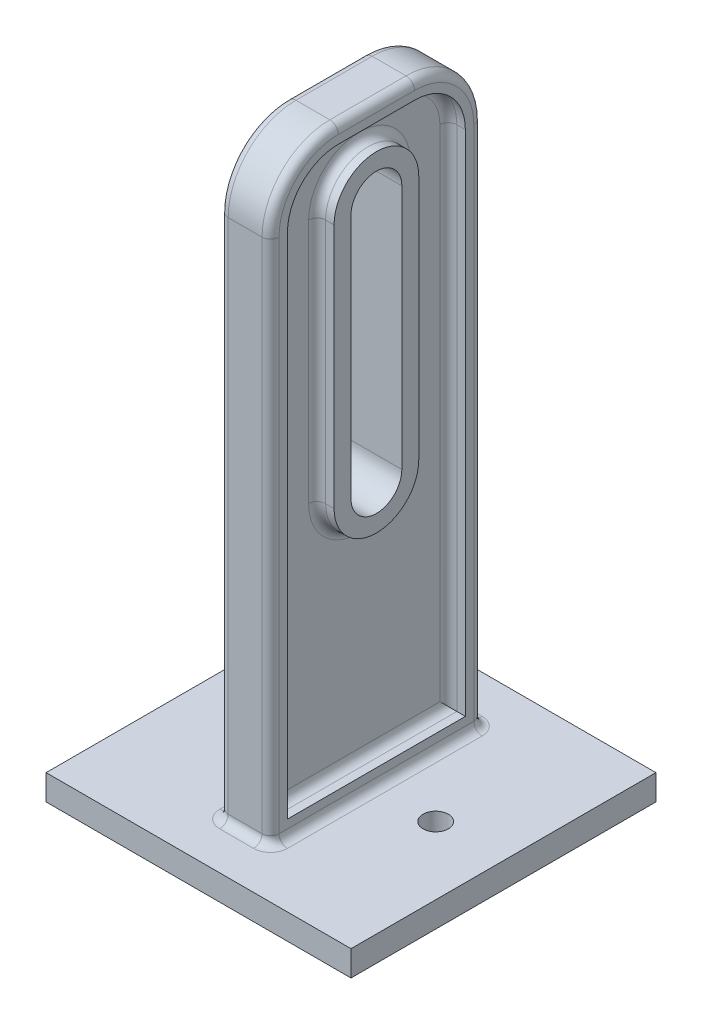
SolidWorks part; units mm, degrees
ref_plane "Front Plane" through (0, 0, 0) normal (0, 0, 1) x (1, 0, 0)
ref_plane "Top Plane" through (0, 0, 0) normal (0, 1, 0) x (1, 0, 0)
ref_plane "Right Plane" through (0, 0, 0) normal (1, 0, 0) x (0, 0, -1)
sketch "Sketch1" plane through (0, 0, 0) normal (0, 1, 0) x (1, 0, 0)
  line L1 (-18, 18) -> (18, 18)
  line L2 (-18, 18) -> (-18, -18)
  line L3 (-18, -18) -> (18, -18)
  line L4 (18, 18) -> (18, -18)
  line L5 (-18, 18) -> (18, -18) construction
  line L6 (-18, -18) -> (18, 18) construction
  point P0 (0, 0)
  dimension "D1" = 36
extrude "Boss-Extrude1" add sketch "Sketch1" along normal blind 3
sketch "Sketch2" plane through (0, 3, 0) normal (0, 1, 0) x (1, 0, 0)
  line L0 (-10, 0) -> (10, 0) construction
  circle A0 centre (-10, 0) radius 1.5
  circle A1 centre (10, 0) radius 1.5
  dimension "D1" = 3
  dimension "D2" = 20
extrude "Cut-Extrude1" cut sketch "Sketch2" against normal through all
sketch "Sketch3" plane through (0, 3, 0) normal (0, 1, 0) x (1, 0, 0)
  line L1 (-3, 12.5) -> (3, 12.5)
  line L2 (-3, 12.5) -> (-3, -12.5)
  line L3 (-3, -12.5) -> (3, -12.5)
  line L4 (3, 12.5) -> (3, -12.5)
  line L5 (-3, 12.5) -> (3, -12.5) construction
  line L6 (-3, -12.5) -> (3, 12.5) construction
  point P0 (0, 0)
  dimension "D1" = 6
  dimension "D2" = 25
extrude "Boss-Extrude2" add sketch "Sketch3" along normal blind 70
sketch "Sketch4" plane through (-3, 0, 0) normal (-1, 0, 0) x (0, 0, 1)
  line L0 (-12.5, 73) -> (12.5, 73) construction
  line L2 (-3, 63) -> (-3, 34)
  line L4 (3, 63) -> (3, 34)
  arc A0 (3, 63) -> (-3, 63) centre (0, 63) ccw
  arc A1 (-3, 34) -> (3, 34) centre (0, 34) ccw
  point P8 (0, 0)
  point P9 (0, 0)
  dimension "D1" = 3
  dimension "D3" = 29
  dimension "D2" = 10
extrude "Cut-Extrude2" cut sketch "Sketch4" against normal through all
fillet "Fillet1" radius 8 2 edges at (0, 73, -12.5) (0, 73, 12.5)
sketch "Sketch5" plane through (-3, 0, 0) normal (-1, 0, 0) x (0, 0, 1)
  line L18 (5, 34) -> (5, 63)
  line L19 (-5, 63) -> (-5, 34)
  line L20 (5, 34) -> (5, 63)
  line L21 (-5, 63) -> (-5, 34)
  line L37 (-10.5, 5) -> (10.5, 5)
  line L38 (10.5, 5) -> (10.5, 65)
  line L39 (4.5, 71) -> (-4.5, 71)
  line L40 (-10.5, 65) -> (-10.5, 5)
  line L41 (-10.5, 5) -> (10.5, 5)
  line L42 (10.5, 5) -> (10.5, 65)
  line L43 (4.5, 71) -> (-4.5, 71)
  line L44 (-10.5, 65) -> (-10.5, 5)
  arc A9 (5, 63) -> (-5, 63) centre (0, 63) ccw
  arc A10 (-5, 34) -> (5, 34) centre (0, 34) ccw
  arc A11 (5, 63) -> (-5, 63) centre (0, 63) ccw
  arc A12 (-5, 34) -> (5, 34) centre (0, 34) ccw
  arc A21 (10.5, 65) -> (4.5, 71) centre (4.5, 65) ccw
  arc A22 (-4.5, 71) -> (-10.5, 65) centre (-4.5, 65) ccw
  arc A23 (10.5, 65) -> (4.5, 71) centre (4.5, 65) ccw
  arc A24 (-4.5, 71) -> (-10.5, 65) centre (-4.5, 65) ccw
  dimension "D1" = 2
  dimension "D2" = 2
extrude "Cut-Extrude3" cut sketch "Sketch5" against normal blind 2
mirror "Mirror1" about plane through (0, 0, 0) normal (1, 0, 0) of "Cut-Extrude3"
fillet "Fillet2" radius 1 34 edges at (0, 3, 12.5) (0, 3, -12.5) (1, 48.5, -5) (1, 68, 0) (1, 48.5, 5) (3, 34, 12.5) (3, 70.6569, 10.1569) (3, 73, 0) (3, 70.6569, -10.1569) (1, 35, -10.5) (1, 69.2426, -8.7426) (1, 71, 0) (1, 69.2426, 8.7426) (-1, 35, 10.5) (-1, 69.2426, 8.7426) (-1, 71, 0) (-1, 69.2426, -8.7426) (-3, 34, -12.5) (-3, 70.6569, -10.1569) (-3, 34, 12.5) (-3, 70.6569, 10.1569) (-1, 48.5, -5) (-1, 68, 0) (-1, 48.5, 5) (1, 29, 0) (3, 34, -12.5) (1, 35, 10.5) (1, 5, 0) (3, 3, 0) (-3, 3, 0) (-1, 35, -10.5) (-1, 5, 0) (-3, 73, 0) (-1, 29, 0)
